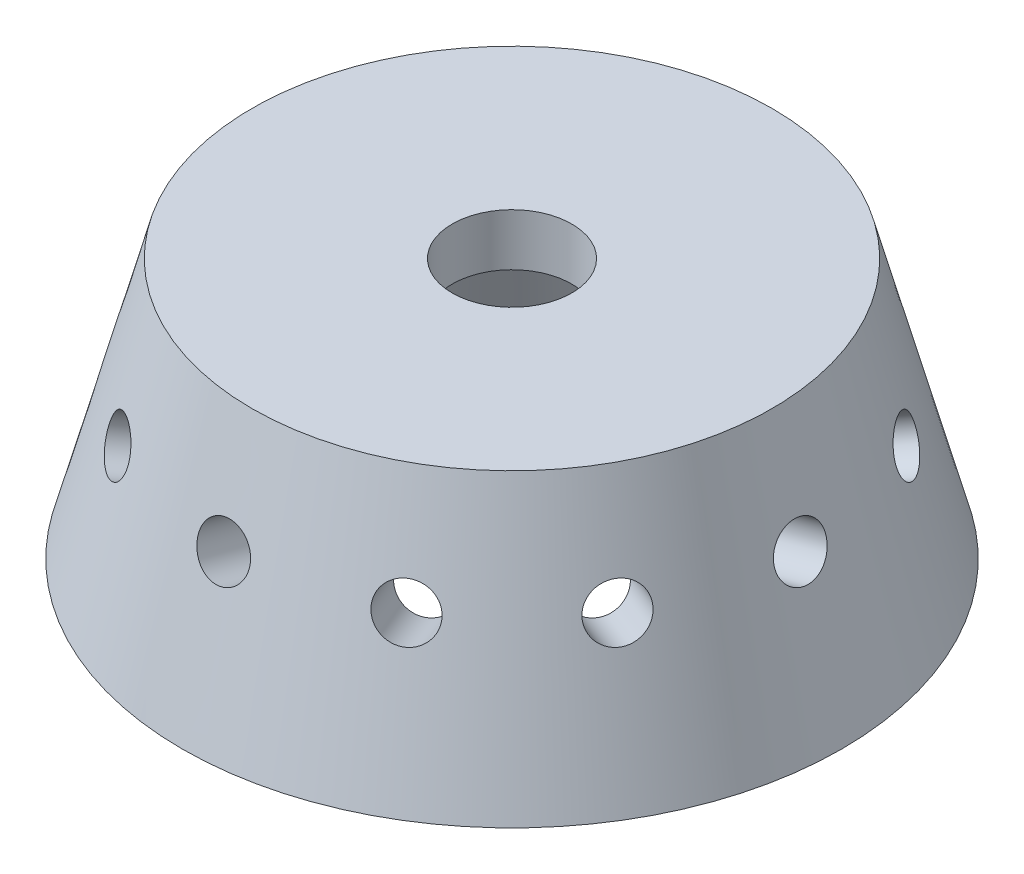
SolidWorks part; units mm, degrees
ref_plane "Front Plane" through (0, 0, 0) normal (0, 0, 1) x (1, 0, 0)
ref_plane "Top Plane" through (0, 0, 0) normal (0, 1, 0) x (1, 0, 0)
ref_plane "Right Plane" through (0, 0, 0) normal (1, 0, 0) x (0, 0, -1)
sketch "Sketch6" plane through (0, 0, 0) normal (0, 0, 1) x (1, 0, 0)
  line L2 (32.5026, -28) -> (25, 0)
  line L3 (25, 0) -> (0, 0)
  line L5 (26, -27.3923) -> (20, -5)
  line L6 (20, -5) -> (0, -5)
  line L7 (0, -5) -> (0, 0)
  line L8 (0, -5) -> (0, -27.3923) construction
  line L9 (0, -27.3923) -> (26, -27.3923) construction
  line L10 (32.5026, -28) -> (32.5026, -10.5) construction
  line L11 (32.5026, -10.5) -> (27.8135, -10.5) construction
  line L12 (32.5026, -28) -> (32.5026, -30)
  line L13 (32.5026, -30) -> (0, -30)
  line L14 (0, -27.3923) -> (0, -30)
  line L15 (0, -27.3923) -> (26, -27.3923)
  dimension "D2" = 5
  dimension "D3" = 25
  dimension "D6" = 17.5
  dimension "D4" = 20
  dimension "D1" = 105
  dimension "D5" = 30
  dimension "D7" = 2
  dimension "D8" = 26
revolve "Revolve2" add sketch "Sketch6" angle 360 about L7
ref_plane "Plane1" through (23.3253, 6.25, 0) normal (0.9659, 0.2588, 0) x (0, 0, -1)
sketch "Sketch11" plane through (0, 0, 0) normal (0, 1, 0) x (1, 0, 0)
  line L0 (-25, 0) -> (25, 0) construction
  circle A0 centre (0, 0) radius 5.75
  circle A2 centre (0, 0) radius 25 construction
  dimension "D1" = 11.5
extrude "Cut-Extrude1" cut sketch "Sketch11" against normal through all
sketch "Sketch24" plane through (23.3253, 6.25, 0) normal (0.9659, 0.2588, 0) x (0, 0, -1)
  circle A0 centre (0, -17.3409) radius 2.5
  dimension "D1" = 5
extrude "Cut-Extrude4" cut sketch "Sketch24" against normal blind 10
pattern_circular "CirPattern1" count 12 over 360 about axis through (0, -28, 0) along (0, -1, 0) of "Cut-Extrude4"
sketch "Sketch25" plane through (0, -30, 0) normal (0, -1, 0) x (1, 0, 0)
  circle A0 centre (0, 0) radius 40
  dimension "D1" = 80
extrude "Cut-Extrude5" cut sketch "Sketch25" against normal blind 5
equation "\"height\"= 3cm"
equation "\"D6@Sketch6\"=\"height\"/2 + 2.5"
